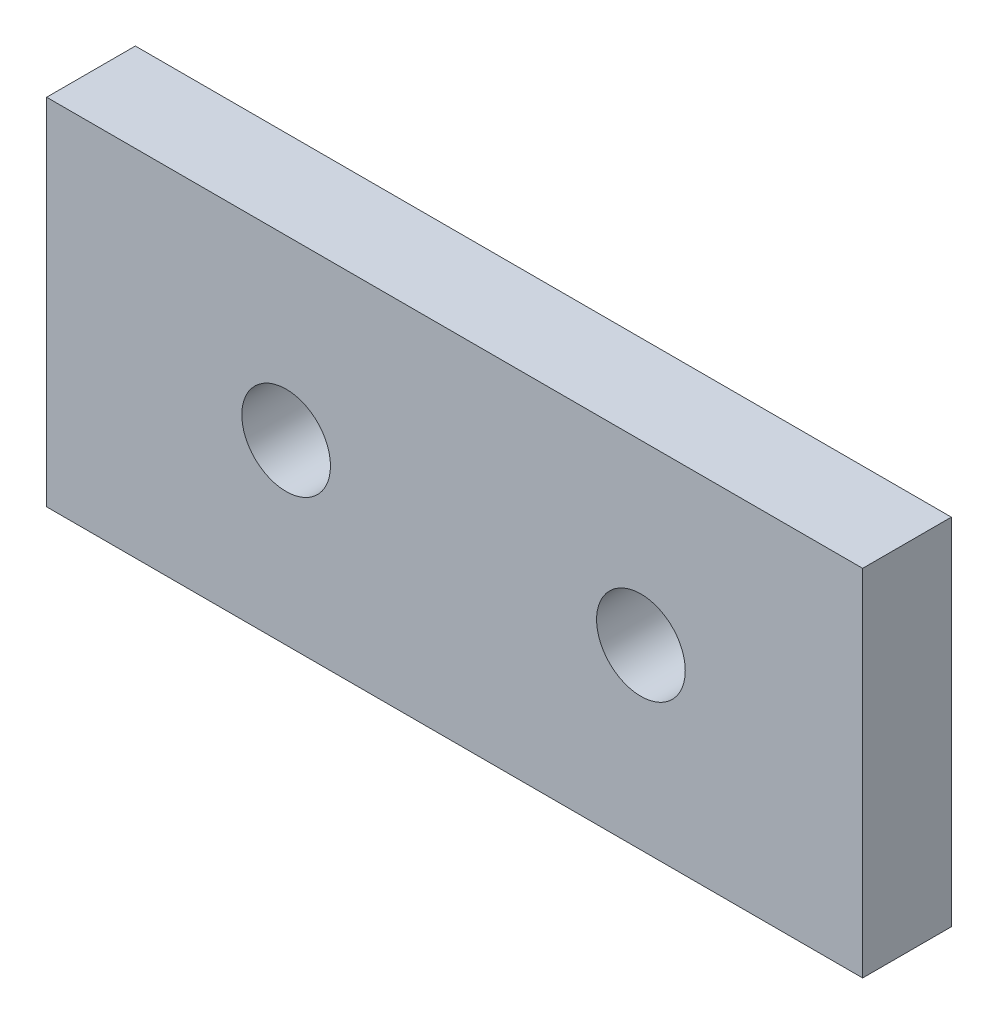
SolidWorks part; units mm, degrees
ref_plane "Płaszczyzna przednia" through (0, 0, 0) normal (0, 0, 1) x (1, 0, 0)
ref_plane "Płaszczyzna górna" through (0, 0, 0) normal (0, 1, 0) x (1, 0, 0)
ref_plane "Płaszczyzna prawa" through (0, 0, 0) normal (1, 0, 0) x (0, 0, -1)
sketch "Szkic1" plane through (0, 0, 0) normal (0, 0, 1) x (1, 0, 0)
  line L1 (-46, 20) -> (46, 20)
  line L2 (-46, 20) -> (-46, -20)
  line L3 (-46, -20) -> (46, -20)
  line L4 (46, 20) -> (46, -20)
  line L5 (-46, 20) -> (46, -20) construction
  line L6 (-46, -20) -> (46, 20) construction
  circle A0 centre (21, 0) radius 5
  circle A1 centre (-19, 0) radius 5
  point P0 (0, 0)
  dimension "D3" = 10
  dimension "D4" = 10
  dimension "D1" = 40
  dimension "D2" = 92
  dimension "D5" = 25
  dimension "D6" = 40
extrude "Dodanie-wyciągnięcie1" add sketch "Szkic1" along normal blind 10
